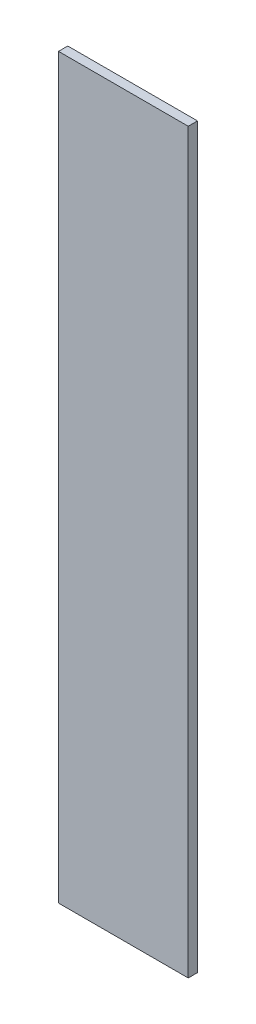
SolidWorks part; units mm, degrees
ref_plane "Front Plane" through (0, 0, 0) normal (1, 0, 0) x (0, 1, 0)
ref_plane "Top Plane" through (0, 0, 0) normal (0, 0, 1) x (0, 1, 0)
ref_plane "Right Plane" through (0, 0, 0) normal (0, 1, 0) x (-1, 0, 0)
sketch "Sketch2" plane through (0, 0, 0) normal (0, 0, 1) x (0, 1, 0)
  line L1 (0, 0) -> (505.46, 0)
  line L2 (0, 0) -> (0, 88.9)
  line L3 (0, 88.9) -> (505.46, 88.9)
  line L4 (505.46, 0) -> (505.46, 88.9)
  dimension "D1" = 88.9
  dimension "D2" = 505.46
extrude "Boss-Extrude1" add sketch "Sketch2" along normal blind 6.35
